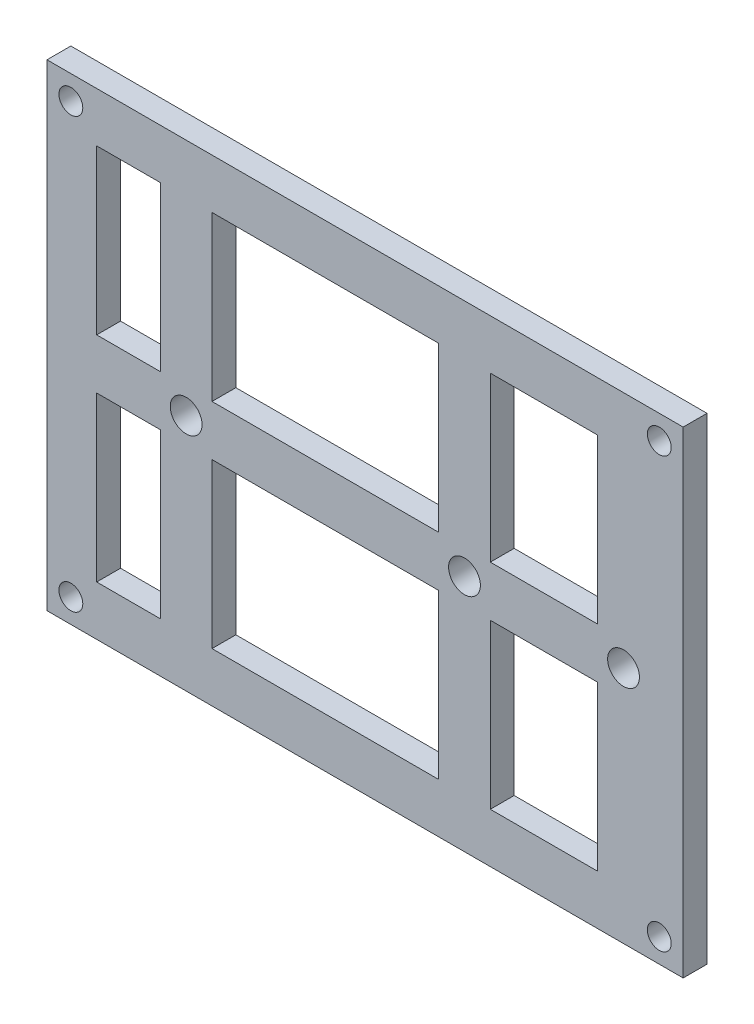
SolidWorks part; units mm, degrees
ref_plane "Front Plane" through (0, 0, 0) normal (0, 0, 1) x (1, 0, 0)
ref_plane "Top Plane" through (0, 0, 0) normal (0, 1, 0) x (1, 0, 0)
ref_plane "Right Plane" through (0, 0, 0) normal (1, 0, 0) x (0, 0, -1)
sketch "Sketch1" plane through (0, 0, 0) normal (0, 0, 1) x (1, 0, 0)
  line L0 (0, 0) -> (40, 0) construction
  line L1 (-40, 30) -> (40, 30)
  line L2 (-40, 30) -> (-40, -30)
  line L3 (-40, -30) -> (40, -30)
  line L4 (40, 30) -> (40, -30)
  line L5 (-40, 30) -> (40, -30) construction
  line L6 (-40, -30) -> (40, 30) construction
  line L7 (15.75, -3.1645) -> (29.25, -3.1645)
  line L8 (0, 0) -> (-40, 0) construction
  line L9 (-19.25, 23.75) -> (9.25, 23.75)
  line L18 (0, 30) -> (0, -30) construction
  line L19 (-19.25, 23.75) -> (-19.25, 3.1645)
  line L20 (-19.25, 3.1645) -> (9.25, 3.1645)
  line L21 (9.25, 23.75) -> (9.25, 3.1645)
  line L22 (15.75, 23.75) -> (29.25, 23.75)
  line L23 (15.75, 23.75) -> (15.75, 3.1645)
  line L24 (15.75, 3.1645) -> (29.25, 3.1645)
  line L25 (29.25, 23.75) -> (29.25, 3.1645)
  line L26 (-33.75, 23.75) -> (-25.75, 23.75)
  line L27 (-33.75, 23.75) -> (-33.75, 3.1645)
  line L28 (-33.75, 3.1645) -> (-25.75, 3.1645)
  line L29 (-25.75, 23.75) -> (-25.75, 3.1645)
  line L30 (29.25, -23.75) -> (29.25, -3.1645)
  line L31 (15.75, -23.75) -> (29.25, -23.75)
  line L32 (15.75, -23.75) -> (15.75, -3.1645)
  line L33 (-19.25, -3.1645) -> (9.25, -3.1645)
  line L34 (9.25, -23.75) -> (9.25, -3.1645)
  line L35 (-19.25, -23.75) -> (9.25, -23.75)
  line L36 (-19.25, -23.75) -> (-19.25, -3.1645)
  line L37 (-33.75, -3.1645) -> (-25.75, -3.1645)
  line L38 (-33.75, -23.75) -> (-33.75, -3.1645)
  line L39 (-25.75, -23.75) -> (-25.75, -3.1645)
  line L40 (-33.75, -23.75) -> (-25.75, -23.75)
  circle A0 centre (-37, 27) radius 1.5
  circle A1 centre (-37, -27) radius 1.5
  circle A2 centre (37, -27) radius 1.5
  circle A3 centre (37, 27) radius 1.5
  circle A6 centre (32.5, 0) radius 2
  circle A7 centre (12.5, 0) radius 2
  circle A8 centre (-22.5, 0) radius 2
  point P0 (0, 0)
  dimension "D11" = 3
  dimension "D12" = 3
  dimension "D13" = 3
  dimension "D14" = 3.25
  dimension "D15" = 3.25
  dimension "D5" = 4
  dimension "D6" = 4
  dimension "D7" = 20
  dimension "D8" = 12.5
  dimension "D9" = 35
  dimension "D18" = 4
  dimension "D1" = 60
  dimension "D2" = 80
  dimension "D3" = 3.25
  dimension "D4" = 3.25
  dimension "D10" = 6.25
  dimension "D16" = 6.25
  dimension "D17" = 3.25
extrude "Boss-Extrude1" add sketch "Sketch1" along normal blind 3
